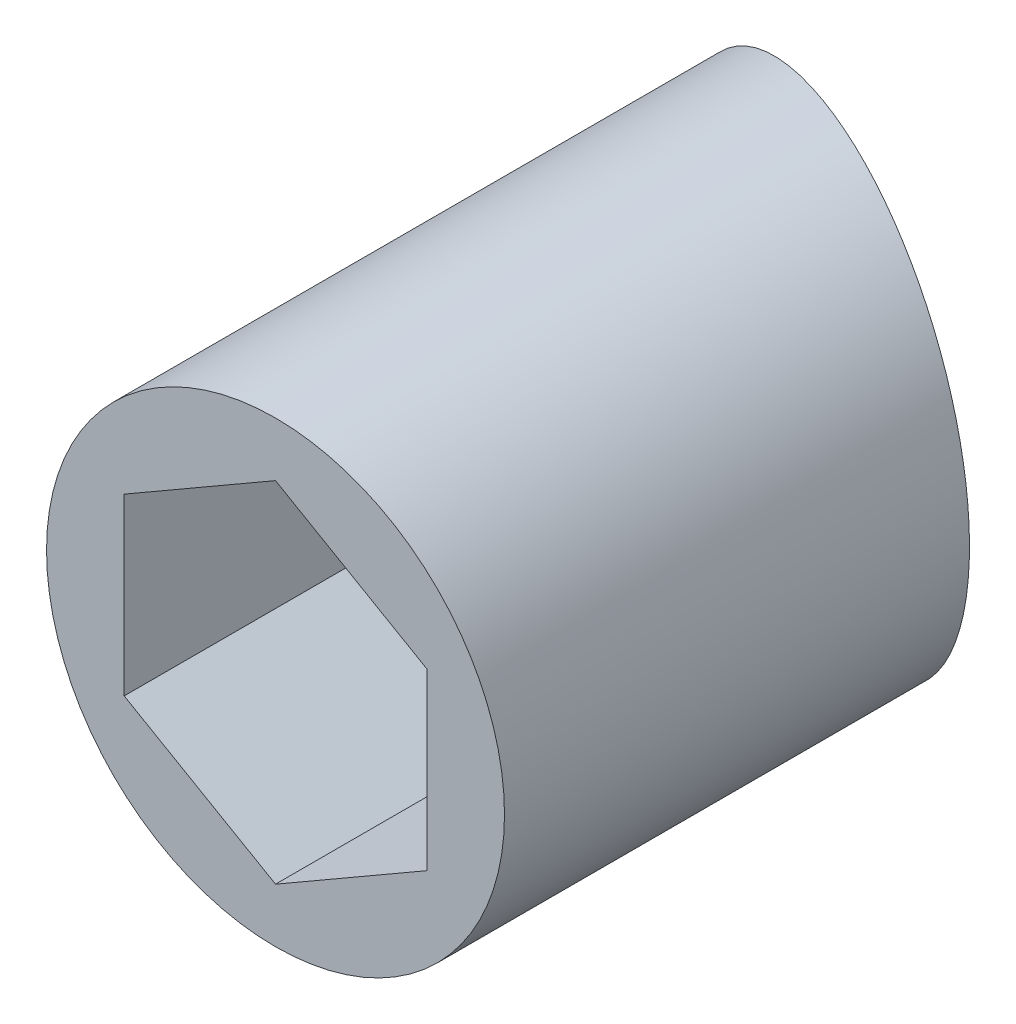
SolidWorks part; units mm, degrees
ref_plane "Спереди" through (0, 0, 0) normal (0, 0, 1) x (1, 0, 0)
ref_plane "Сверху" through (0, 0, 0) normal (0, 1, 0) x (1, 0, 0)
ref_plane "Справа" through (0, 0, 0) normal (1, 0, 0) x (0, 0, -1)
sketch "Эскиз1" plane through (0, 0, 0) normal (0, 0, 1) x (1, 0, 0)
  circle A0 centre (0, 0) radius 4.35
  dimension "D1" = 8.7
extrude "Бобышка-Вытянуть1" add sketch "Эскиз1" along normal blind 12
sketch "Эскиз2" plane through (0, 0, 12) normal (0, 0, 1) x (1, 0, 0)
  line L1 (0, 3.3198) -> (-2.875, 1.6599)
  line L2 (-2.875, 1.6599) -> (-2.875, -1.6599)
  line L3 (-2.875, -1.6599) -> (0, -3.3198)
  line L4 (0, -3.3198) -> (2.875, -1.6599)
  line L5 (2.875, -1.6599) -> (2.875, 1.6599)
  line L6 (2.875, 1.6599) -> (0, 3.3198)
  circle A0 centre (0, 0) radius 2.875 construction
  point P1 (0, 0)
  dimension "D1" = 5.75
extrude "Углубление под гайку" cut sketch "Эскиз2" against normal blind 9
sketch "Эскиз3" plane through (0, 0, 0) normal (0, 1, 0) x (1, 0, 0)
  line L0 (-4.35, 0) -> (4.35, -3.1665)
  line L1 (4.35, -12) -> (4.35, 0) construction
  line L2 (4.35, -3.1665) -> (4.35, 0)
  line L3 (4.35, 0) -> (-4.35, 0)
  dimension "D1" = 20
extrude "Срез толкателя" cut sketch "Эскиз3" against normal up to next and the other way up to next
